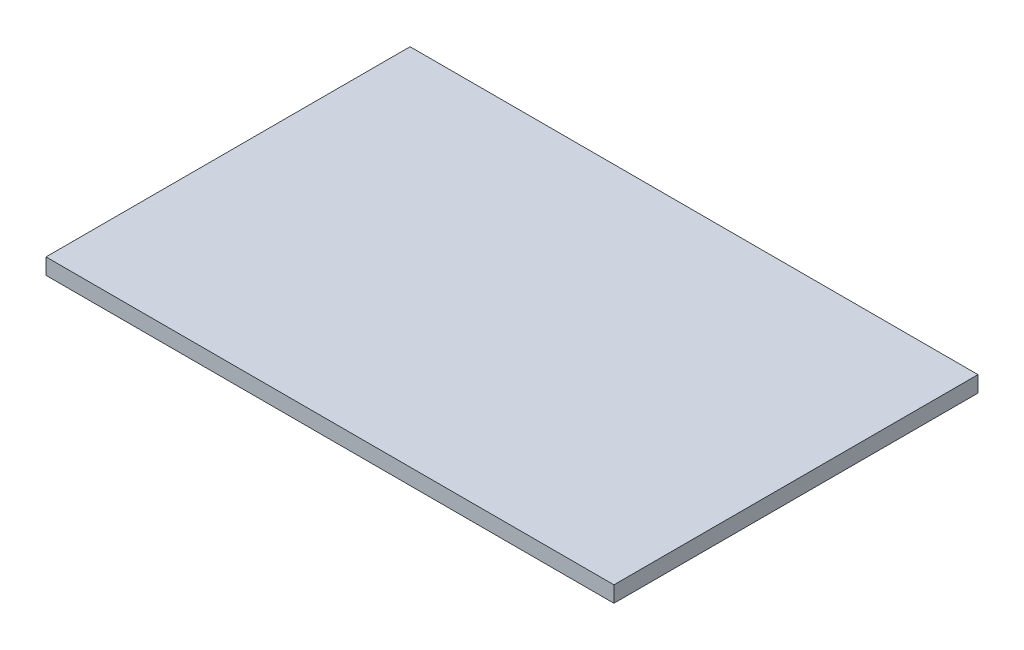
SolidWorks part; units mm, degrees
ref_plane "前视基准面" through (0, 0, 0) normal (0, 0, 1) x (1, 0, 0)
ref_plane "上视基准面" through (0, 0, 0) normal (0, 1, 0) x (1, 0, 0)
ref_plane "右视基准面" through (0, 0, 0) normal (1, 0, 0) x (0, 0, -1)
other "Configuration Table"
sketch "草图1" plane through (0, 0, 0) normal (0, 1, 0) x (1, 0, 0)
  line L1 (0, 0) -> (39, 0)
  line L2 (0, 0) -> (0, 25)
  line L3 (0, 25) -> (39, 25)
  line L4 (39, 0) -> (39, 25)
  line L5 (0, 0) -> (39, 25) construction
  line L6 (0, 25) -> (39, 0) construction
  point P4 (19.5, 12.5)
  dimension "D1" = 39
  dimension "D2" = 25
extrude "凸台-拉伸1" add sketch "草图1" along normal blind 1.1
